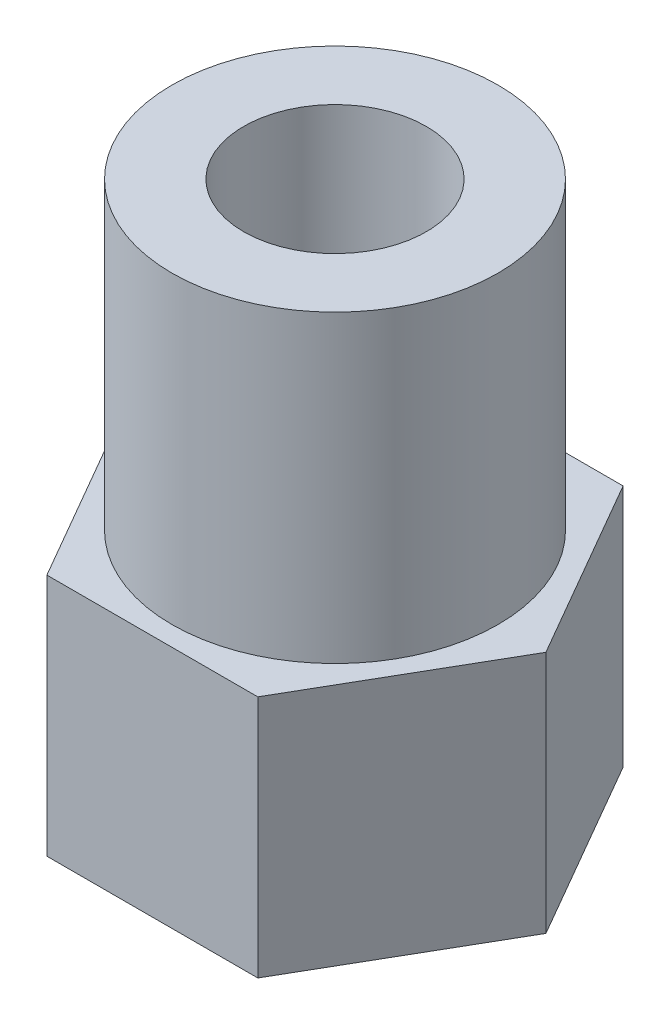
SolidWorks part; units mm, degrees
ref_plane "前视基准面" through (0, 0, 0) normal (0, 0, 1) x (1, 0, 0)
ref_plane "上视基准面" through (0, 0, 0) normal (0, 1, 0) x (1, 0, 0)
ref_plane "右视基准面" through (0, 0, 0) normal (1, 0, 0) x (0, 0, -1)
sketch "Sketch2" plane through (0, 0, 0) normal (0, 1, 0) x (1, 0, 0)
  line L1 (3.465, 6.0016) -> (-3.465, 6.0016)
  line L2 (-3.465, 6.0016) -> (-6.93, 0)
  line L3 (-6.93, 0) -> (-3.465, -6.0016)
  line L4 (-3.465, -6.0016) -> (3.465, -6.0016)
  line L5 (3.465, -6.0016) -> (6.93, 0)
  line L6 (6.93, 0) -> (3.465, 6.0016)
  circle A0 centre (0, 0) radius 6.0016 construction
  dimension "D1" = 0
  dimension "D2" = 6.93
extrude "Boss-Extrude1" add sketch "Sketch2" along normal blind 8
sketch "Sketch3" plane through (0, 8, 0) normal (0, 1, 0) x (1, 0, 0)
  circle A0 centre (0, 0) radius 5.3552
extrude "Boss-Extrude2" add sketch "Sketch3" along normal blind 10
sketch "Sketch4" plane through (0, 18, 0) normal (0, 1, 0) x (1, 0, 0)
  circle A0 centre (0, 0) radius 3
  dimension "D1" = 6
extrude "Cut-Extrude1" cut sketch "Sketch4" against normal blind 20
